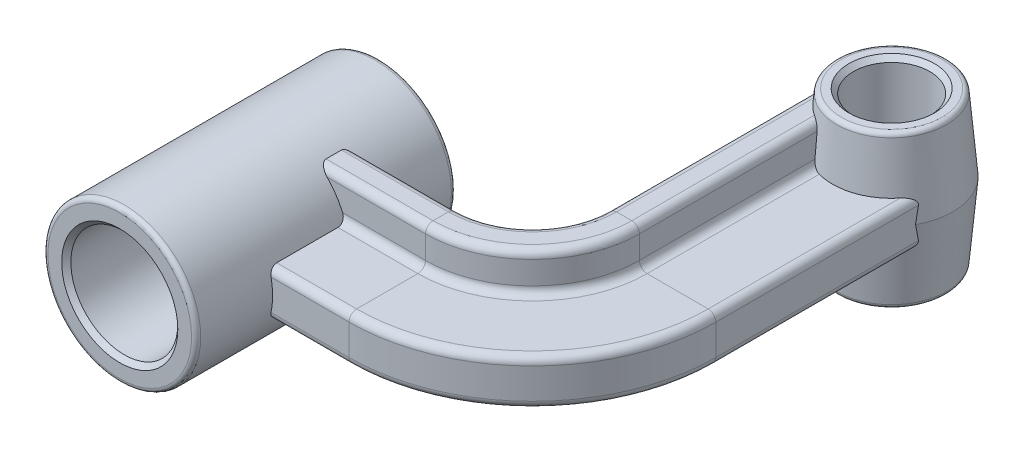
SolidWorks part; units mm, degrees
ref_plane "Front Plane" through (0, 0, 0) normal (0, 0, 1) x (1, 0, 0)
ref_plane "Top Plane" through (0, 0, 0) normal (0, 1, 0) x (1, 0, 0)
ref_plane "Right Plane" through (0, 0, 0) normal (1, 0, 0) x (0, 0, -1)
sketch "Sketch1" plane through (0, 0, 0) normal (0, 0, 1) x (1, 0, 0)
  circle A0 centre (0, 0) radius 50
  dimension "D1" = 100
extrude "Boss-Extrude1" add sketch "Sketch1" along normal blind 120 and the other way blind 50
sketch "Sketch2" plane through (0, 0, 0) normal (1, 0, 0) x (0, 0, -1)
  line L0 (0, -35) -> (0, 35)
  line L1 (-5, 40) -> (-15, 40)
  line L2 (-20, 35) -> (-20, 20)
  line L3 (-25, 15) -> (-65, 15)
  line L5 (-70, -10) -> (-70, 10)
  line L6 (-25, -15) -> (-65, -15)
  line L7 (-20, -35) -> (-20, -20)
  line L8 (-5, -40) -> (-15, -40)
  arc A0 (-20, 20) -> (-25, 15) centre (-25, 20) cw
  arc A1 (-15, 40) -> (-20, 35) centre (-15, 35) ccw
  arc A2 (0, 35) -> (-5, 40) centre (-5, 35) ccw
  arc A3 (-5, -40) -> (0, -35) centre (-5, -35) ccw
  arc A4 (-20, -35) -> (-15, -40) centre (-15, -35) ccw
  arc A5 (-25, -15) -> (-20, -20) centre (-25, -20) cw
  arc A6 (-65, -15) -> (-70, -10) centre (-65, -10) cw
  arc A7 (-65, 15) -> (-70, 10) centre (-65, 10) ccw
  dimension "D1" = 5
  dimension "D2" = 20
  dimension "D3" = 70
  dimension "D4" = 15
  dimension "D5" = 40
  dimension "D6" = 15
sketch "Sketch3" plane through (0, 0, 0) normal (0, 1, 0) x (1, 0, 0)
  line L0 (0, 0) -> (100, 0)
  line L1 (150, 50) -> (150, 200)
  arc A0 (100, 0) -> (150, 50) centre (100, 50) ccw
  dimension "D1" = 50
  dimension "D2" = 150
  dimension "D3" = 200
sweep "Sweep1" add profiles "Sketch2" path "Sketch3"
sketch "Sketch4" plane through (0, 0, 0) normal (0, 1, 0) x (1, 0, 0)
  line L2 (175, 200) -> (215, 200) construction
  circle A0 centre (185, 200) radius 40
  dimension "D1" = 80
  dimension "D2" = 185
extrude "Boss-Extrude4" add sketch "Sketch4" along normal mid plane 100 draft 5
sketch "Sketch5" plane through (0, 50, 0) normal (0, 1, 0) x (1, 0, 0)
  circle A0 centre (185, 200) radius 25
extrude "Cut-Extrude1" cut sketch "Sketch5" against normal through all
sketch "Sketch6" plane through (0, 0, 120) normal (0, 0, 1) x (1, 0, 0)
  circle A0 centre (0, 0) radius 35
extrude "Cut-Extrude2" cut sketch "Sketch6" against normal through all
fillet "Fillet1" radius 3 4 edges at (185, -50, -164.3744) (185, 50, -164.3744) (50, 0, -50) (50, 0, 120)
chamfer "Chamfer1" distance 3 angle 45 4 edges at (35, 0, 120) (35, 0, -50) (185, -50, -175) (185, 50, -175)
